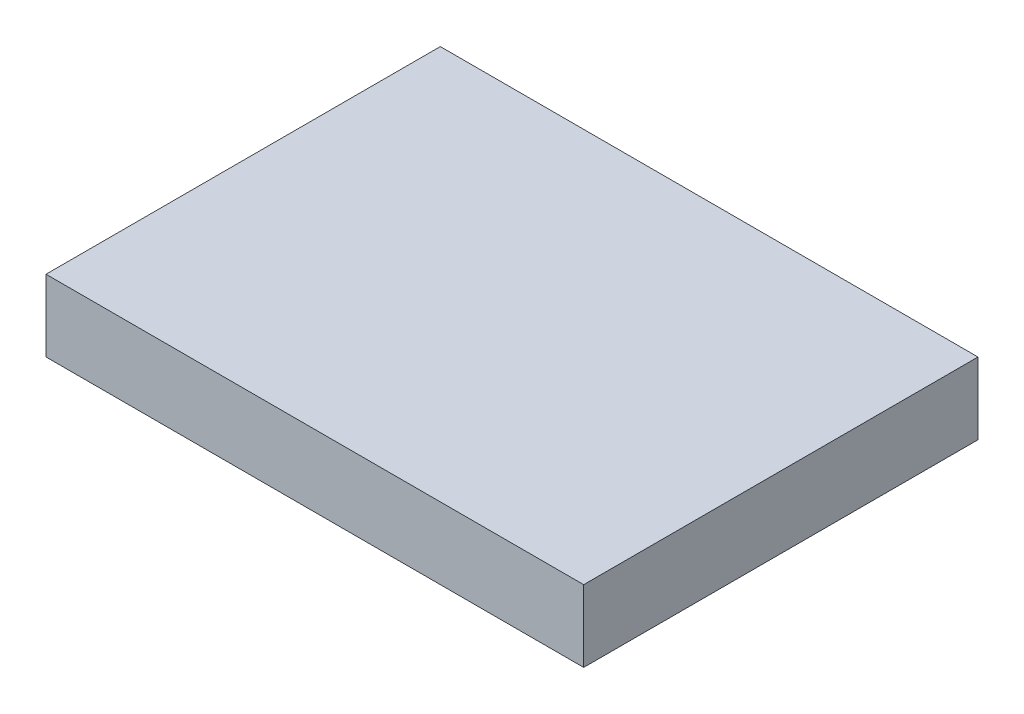
SolidWorks part; units mm, degrees
ref_plane "Front" through (0, 0, 0) normal (0, 0, 1) x (1, 0, 0)
ref_plane "Top" through (0, 0, 0) normal (0, 1, 0) x (1, 0, 0)
ref_plane "Right" through (0, 0, 0) normal (1, 0, 0) x (0, 0, -1)
sketch "Sketch1" plane through (0, 0, 0) normal (0, 1, 0) x (1, 0, 0)
  line L1 (-37.5, -27.5) -> (37.5, -27.5)
  line L2 (-37.5, -27.5) -> (-37.5, 27.5)
  line L3 (-37.5, 27.5) -> (37.5, 27.5)
  line L4 (37.5, -27.5) -> (37.5, 27.5)
  line L5 (-37.5, -27.5) -> (37.5, 27.5) construction
  line L6 (-37.5, 27.5) -> (37.5, -27.5) construction
  point P0 (0, 0)
extrude "Boss-Extrude1" add sketch "Sketch1" along normal blind 10
